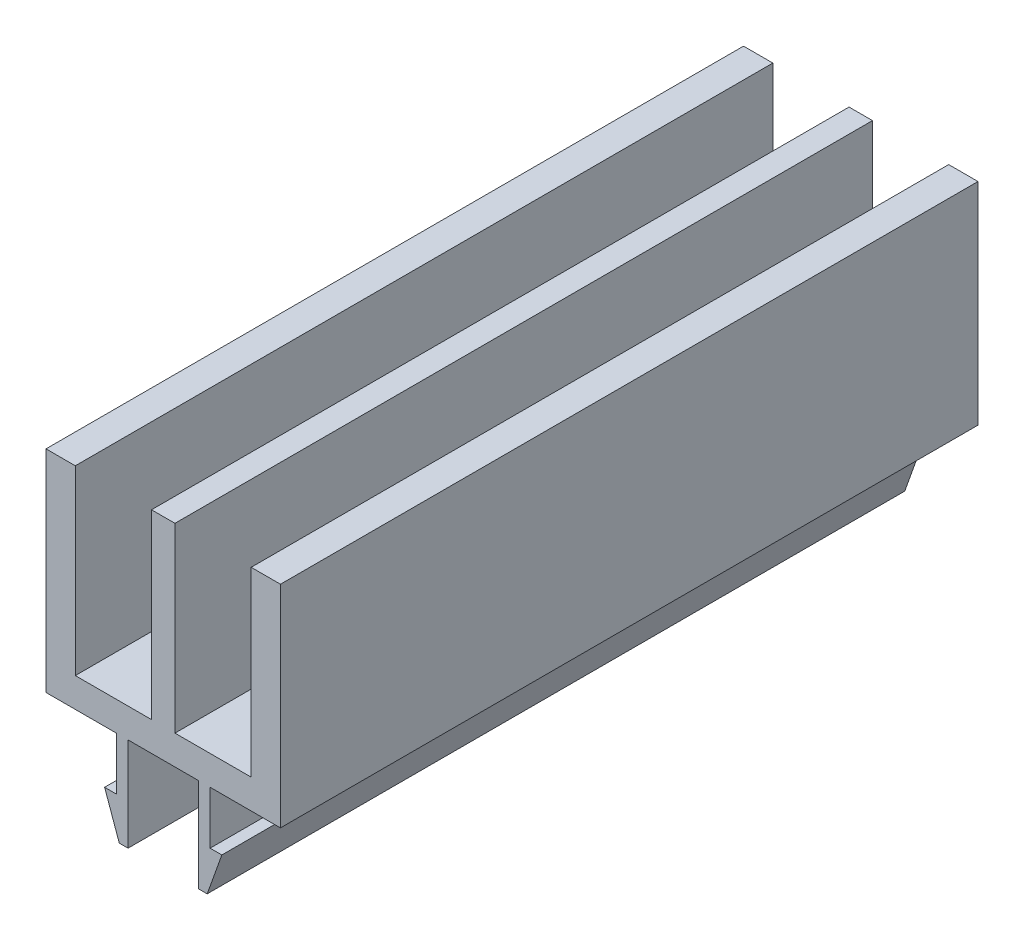
SolidWorks part; units mm, degrees
ref_plane "Plan de face" through (0, 0, 0) normal (0, 0, 1) x (1, 0, 0)
ref_plane "Plan de dessus" through (0, 0, 0) normal (0, 1, 0) x (1, 0, 0)
ref_plane "Plan de droite" through (0, 0, 0) normal (1, 0, 0) x (0, 0, -1)
ref_plane "Plan1" through (0, 0, 50) normal (0, 0, 1) x (1, 0, 0)
sketch "Esquisse1" plane through (0, 0, 50) normal (0, 0, 1) x (1, 0, 0)
  line L0 (-1, 2.5) -> (-7.5, 2.5)
  line L1 (-7.5, 2.5) -> (-7.5, 18)
  line L2 (-7.5, 18) -> (-10, 18)
  line L3 (-10, 18) -> (-10, 0)
  line L4 (-10, 0) -> (-4, 0)
  line L5 (-4, 0) -> (-4, -4.5)
  line L6 (-4, -4.5) -> (-5, -4.5)
  line L7 (-5, -4.5) -> (-3.75, -8)
  line L8 (-3.75, -8) -> (-3, -8)
  line L9 (-3, -8) -> (-3, 0)
  line L10 (-3, 0) -> (3, 0)
  line L11 (3, 0) -> (3, -8)
  line L12 (3, -8) -> (3.75, -8)
  line L13 (3.75, -8) -> (5, -4.5)
  line L14 (5, -4.5) -> (4, -4.5)
  line L15 (4, -4.5) -> (4, 0)
  line L16 (4, 0) -> (10, 0)
  line L17 (10, 0) -> (10, 18)
  line L18 (10, 18) -> (7.5, 18)
  line L19 (7.5, 18) -> (7.5, 2.5)
  line L20 (7.5, 2.5) -> (1, 2.5)
  line L21 (1, 2.5) -> (1, 18)
  line L22 (1, 18) -> (-1, 18)
  line L23 (-1, 18) -> (-1, 2.5)
extrude "Boss.-Extru.1" add sketch "Esquisse1" against normal blind 59.5
